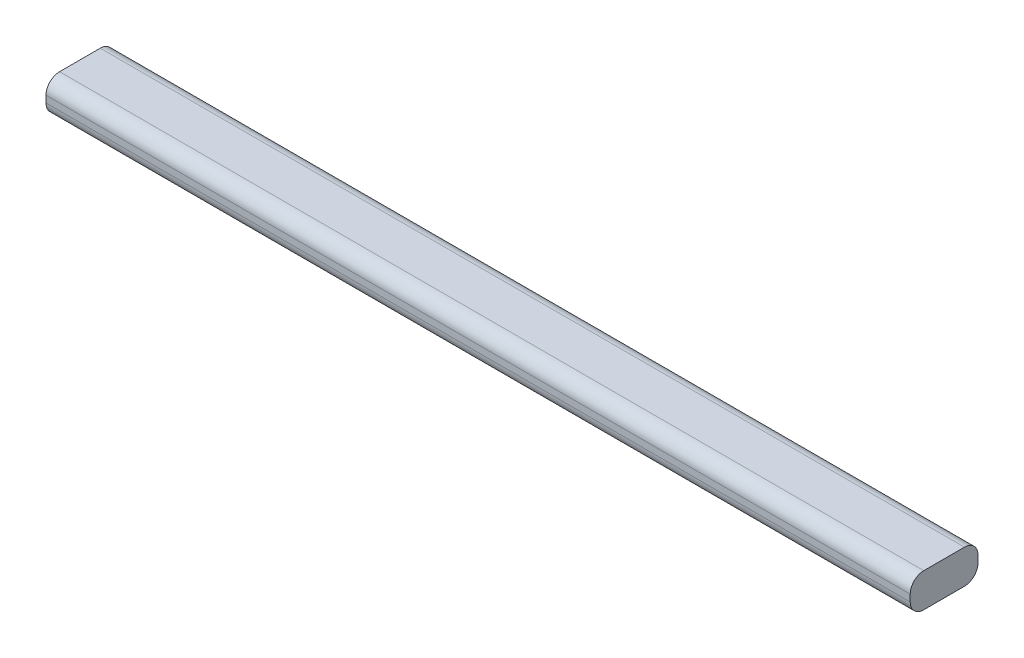
SolidWorks part; units mm, degrees
material "6061-T4 (SS)"
ref_plane "Front Plane" through (0, 0, 0) normal (0, 0, 1) x (1, 0, 0)
ref_plane "Top Plane" through (0, 0, 0) normal (0, 1, 0) x (1, 0, 0)
ref_plane "Right Plane" through (0, 0, 0) normal (1, 0, 0) x (0, 0, -1)
sketch "Sketch1" plane through (0, 0, 0) normal (0, 1, 0) x (1, 0, 0)
  line L0 (-63.75, -5) -> (-63.75, 5)
  line L1 (-63.75, -5) -> (63.75, -5)
  line L2 (-63.75, 5) -> (63.75, 5)
  line L3 (63.75, -5) -> (63.75, 5)
  line L4 (-63.75, -5) -> (63.75, 5) construction
  line L5 (-63.75, 5) -> (63.75, -5) construction
  point P1 (0, 0)
  dimension "D1" = 127.5
  dimension "D2" = 10
extrude "Boss-Extrude1" add sketch "Sketch1" along normal blind 5
fillet "Fillet1" radius 2 1 edges at (0, 5, 5)
fillet "Fillet2" radius 2 1 edges at (0, 0, 5)
fillet "Fillet3" radius 2 1 edges at (0, 5, -5)
fillet "Fillet4" radius 2 1 edges at (0, 0, -5)
